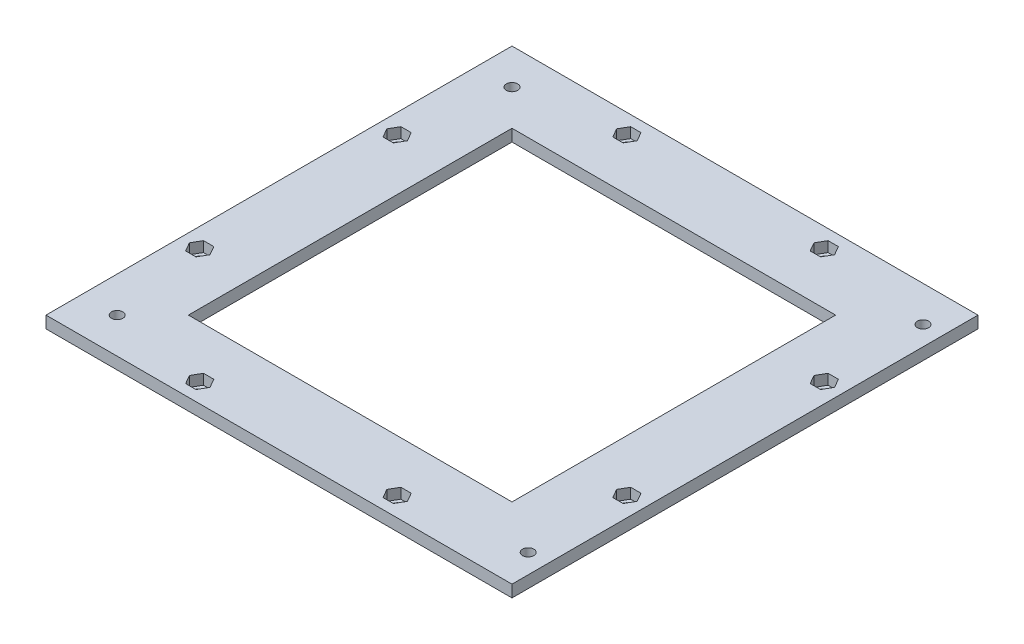
SolidWorks part; units mm, degrees
ref_plane "Alzado" through (0, 0, 0) normal (0, 0, 1) x (1, 0, 0)
ref_plane "Planta" through (0, 0, 0) normal (0, 1, 0) x (1, 0, 0)
ref_plane "Vista lateral" through (0, 0, 0) normal (1, 0, 0) x (0, 0, -1)
sketch "Croquis1" plane through (0, 0, 0) normal (0, 1, 0) x (1, 0, 0)
  line L0 (0, 0) -> (-62.5, 0) construction
  line L1 (-62.5, 0) -> (-62.5, 55) construction
  line L2 (-62.5, 55) -> (-55, 62.5) construction
  line L3 (-55, 62.5) -> (0, 62.5) construction
  line L4 (0, 62.5) -> (0, 0) construction
  line L5 (62.5, 55) -> (62.5, 0) construction
  line L6 (55, 62.5) -> (62.5, 55) construction
  line L7 (0, 62.5) -> (55, 62.5) construction
  line L8 (55, -62.5) -> (0, -62.5) construction
  line L9 (62.5, -55) -> (55, -62.5) construction
  line L10 (62.5, 0) -> (62.5, -55) construction
  line L11 (-62.5, -55) -> (-62.5, 0) construction
  line L12 (-55, -62.5) -> (-62.5, -55) construction
  line L13 (0, -62.5) -> (-55, -62.5) construction
  line L14 (0, -70) -> (0, -62.5) construction
  line L15 (0, 0) -> (-61, 0) construction
  line L16 (0, 0) -> (0, 61) construction
  line L17 (0, 61) -> (-61, 61) construction
  line L18 (-61, 0) -> (-61, 61) construction
  line L19 (0, 0) -> (-61, 0) construction
  line L20 (0, 0) -> (0, -61) construction
  line L21 (0, -61) -> (-61, -61) construction
  line L22 (-61, 0) -> (-61, -61) construction
  line L23 (0, 0) -> (66, 0) construction
  line L24 (0, 0) -> (0, -61) construction
  line L25 (0, -61) -> (66, -61) construction
  line L26 (66, 0) -> (66, -61) construction
  line L27 (0, 0) -> (66, 0) construction
  line L28 (0, 0) -> (0, 61) construction
  line L29 (0, 61) -> (66, 61) construction
  line L30 (66, 0) -> (66, 61) construction
  line L35 (25, -25) -> (-25, 25) construction
  line L36 (25, 25) -> (-25, -25) construction
  line L37 (70, -70) -> (-70, -70)
  line L38 (70, -70) -> (70, 70)
  line L39 (70, 70) -> (-70, 70)
  line L40 (-70, -70) -> (-70, 70)
  line L41 (70, -70) -> (-70, 70) construction
  line L42 (70, 70) -> (-70, -70) construction
  line L43 (-30.5, -66) -> (30.5, -66) construction
  circle A0 centre (-61, 61) radius 1.5
  circle A1 centre (66, 61) radius 1.5
  circle A2 centre (66, -61) radius 1.5
  circle A3 centre (-61, -61) radius 1.5
  circle A4 centre (66, 30.5) radius 1.5
  circle A5 centre (66, -30.5) radius 1.5
  circle A6 centre (-30.5, -66) radius 1.5
  circle A7 centre (30.5, -66) radius 1.5
  circle A8 centre (-30.5, 66) radius 1.5
  circle A9 centre (30.5, 66) radius 1.5
  circle A10 centre (-66, 30.5) radius 1.5
  circle A11 centre (-66, -30.5) radius 1.5
  point P48 (0, -66)
  dimension "D6" = 3
  dimension "D9" = 4
  dimension "D10" = 3
  dimension "D1" = 55
  dimension "D2" = 62.5
  dimension "D4" = 61
  dimension "D5" = 66
  dimension "D7" = 50
  dimension "D8" = 140
  dimension "D11" = 61
  dimension "D3" = 4
extrude "Saliente-Extruir1" add sketch "Croquis1" along normal blind 0.5
sketch "Croquis2" plane through (0, 0.5, 0) normal (0, 1, 0) x (1, 0, 0)
  line L1 (-28.9065, 63.24) -> (-27.313, 66)
  line L2 (-27.313, 66) -> (-28.9065, 68.76)
  line L3 (-28.9065, 68.76) -> (-32.0935, 68.76)
  line L4 (-32.0935, 68.76) -> (-33.687, 66)
  line L5 (-33.687, 66) -> (-32.0935, 63.24)
  line L6 (-32.0935, 63.24) -> (-28.9065, 63.24)
  line L7 (32.0935, 63.24) -> (33.687, 66)
  line L8 (33.687, 66) -> (32.0935, 68.76)
  line L9 (32.0935, 68.76) -> (28.9065, 68.76)
  line L10 (28.9065, 68.76) -> (27.313, 66)
  line L11 (27.313, 66) -> (28.9065, 63.24)
  line L12 (28.9065, 63.24) -> (32.0935, 63.24)
  line L13 (67.5935, 27.74) -> (69.187, 30.5)
  line L14 (69.187, 30.5) -> (67.5935, 33.26)
  line L15 (67.5935, 33.26) -> (64.4065, 33.26)
  line L16 (64.4065, 33.26) -> (62.813, 30.5)
  line L17 (62.813, 30.5) -> (64.4065, 27.74)
  line L18 (64.4065, 27.74) -> (67.5935, 27.74)
  line L19 (67.5935, -33.26) -> (69.187, -30.5)
  line L20 (69.187, -30.5) -> (67.5935, -27.74)
  line L21 (67.5935, -27.74) -> (64.4065, -27.74)
  line L22 (64.4065, -27.74) -> (62.813, -30.5)
  line L23 (62.813, -30.5) -> (64.4065, -33.26)
  line L24 (64.4065, -33.26) -> (67.5935, -33.26)
  line L25 (32.0935, -68.76) -> (33.687, -66)
  line L26 (33.687, -66) -> (32.0935, -63.24)
  line L27 (32.0935, -63.24) -> (28.9065, -63.24)
  line L28 (28.9065, -63.24) -> (27.313, -66)
  line L29 (27.313, -66) -> (28.9065, -68.76)
  line L30 (28.9065, -68.76) -> (32.0935, -68.76)
  line L31 (-28.9065, -68.76) -> (-27.313, -66)
  line L32 (-27.313, -66) -> (-28.9065, -63.24)
  line L33 (-28.9065, -63.24) -> (-32.0935, -63.24)
  line L34 (-32.0935, -63.24) -> (-33.687, -66)
  line L35 (-33.687, -66) -> (-32.0935, -68.76)
  line L36 (-32.0935, -68.76) -> (-28.9065, -68.76)
  line L37 (-64.4065, -33.26) -> (-62.813, -30.5)
  line L38 (-62.813, -30.5) -> (-64.4065, -27.74)
  line L39 (-64.4065, -27.74) -> (-67.5935, -27.74)
  line L40 (-67.5935, -27.74) -> (-69.187, -30.5)
  line L41 (-69.187, -30.5) -> (-67.5935, -33.26)
  line L42 (-67.5935, -33.26) -> (-64.4065, -33.26)
  line L43 (-64.4065, 27.74) -> (-62.813, 30.5)
  line L44 (-62.813, 30.5) -> (-64.4065, 33.26)
  line L45 (-64.4065, 33.26) -> (-67.5935, 33.26)
  line L46 (-67.5935, 33.26) -> (-69.187, 30.5)
  line L47 (-69.187, 30.5) -> (-67.5935, 27.74)
  line L48 (-67.5935, 27.74) -> (-64.4065, 27.74)
  line L49 (-50, 50) -> (50, 50)
  line L50 (-50, 50) -> (-50, -50)
  line L51 (-50, -50) -> (50, -50)
  line L52 (50, 50) -> (50, -50)
  line L53 (-50, 50) -> (50, -50) construction
  line L54 (-50, -50) -> (50, 50) construction
  circle A0 centre (-30.5, 66) radius 2.76 construction
  circle A1 centre (30.5, 66) radius 2.76 construction
  circle A2 centre (66, 30.5) radius 2.76 construction
  circle A3 centre (66, -30.5) radius 2.76 construction
  circle A4 centre (30.5, -66) radius 2.76 construction
  circle A5 centre (-30.5, -66) radius 2.76 construction
  circle A6 centre (-66, -30.5) radius 2.76 construction
  circle A7 centre (-66, 30.5) radius 2.76 construction
  circle A8 centre (66, 61) radius 1.75
  circle A9 centre (-61, 61) radius 1.75
  circle A10 centre (-61, -61) radius 1.75
  circle A11 centre (66, -61) radius 1.75
  point P64 (0, 0)
  dimension "D3" = 3.5
  dimension "D1" = 5.52
  dimension "D2" = 100
extrude "Cortar-Extruir1" cut sketch "Croquis2" against normal blind 10
sketch "Croquis3" plane through (0, 0.5, 0) normal (0, 1, 0) x (1, 0, 0)
  line L0 (-50, -50) -> (50, -50) construction
  line L1 (-50, 50) -> (-50, -50) construction
  line L12 (-33.687, -66) -> (-32.0935, -68.76) construction
  line L13 (-32.0935, -68.76) -> (-28.9065, -68.76) construction
  line L14 (-28.9065, -68.76) -> (-27.313, -66) construction
  line L15 (-27.313, -66) -> (-28.9065, -63.24) construction
  line L16 (-28.9065, -63.24) -> (-32.0935, -63.24) construction
  line L17 (-32.0935, -63.24) -> (-33.687, -66) construction
  line L18 (-67.5935, -33.26) -> (-64.4065, -33.26) construction
  line L19 (-69.187, -30.5) -> (-67.5935, -33.26) construction
  line L20 (-67.5935, -27.74) -> (-69.187, -30.5) construction
  line L21 (-64.4065, -27.74) -> (-67.5935, -27.74) construction
  line L22 (-62.813, -30.5) -> (-64.4065, -27.74) construction
  line L23 (-64.4065, -33.26) -> (-62.813, -30.5) construction
  line L24 (-50, 50) -> (-50, -50)
  line L25 (-50, -50) -> (50, -50)
  line L26 (-33.687, -66) -> (-32.0935, -68.76)
  line L27 (-32.0935, -68.76) -> (-28.9065, -68.76)
  line L28 (-28.9065, -68.76) -> (-27.313, -66)
  line L29 (-27.313, -66) -> (-28.9065, -63.24)
  line L30 (-28.9065, -63.24) -> (-32.0935, -63.24)
  line L31 (-32.0935, -63.24) -> (-33.687, -66)
  line L32 (-67.5935, -33.26) -> (-64.4065, -33.26)
  line L33 (-69.187, -30.5) -> (-67.5935, -33.26)
  line L34 (-67.5935, -27.74) -> (-69.187, -30.5)
  line L35 (-64.4065, -27.74) -> (-67.5935, -27.74)
  line L36 (-62.813, -30.5) -> (-64.4065, -27.74)
  line L37 (-64.4065, -33.26) -> (-62.813, -30.5)
  line L38 (28.9065, 63.24) -> (32.0935, 63.24) construction
  line L39 (32.0935, 63.24) -> (33.687, 66) construction
  line L40 (33.687, 66) -> (32.0935, 68.76) construction
  line L41 (32.0935, 68.76) -> (28.9065, 68.76) construction
  line L42 (28.9065, 68.76) -> (27.313, 66) construction
  line L43 (27.313, 66) -> (28.9065, 63.24) construction
  line L44 (-33.687, 66) -> (-32.0935, 63.24) construction
  line L45 (-32.0935, 68.76) -> (-33.687, 66) construction
  line L46 (-28.9065, 68.76) -> (-32.0935, 68.76) construction
  line L47 (-27.313, 66) -> (-28.9065, 68.76) construction
  line L48 (-28.9065, 63.24) -> (-27.313, 66) construction
  line L49 (-32.0935, 63.24) -> (-28.9065, 63.24) construction
  line L50 (62.813, 30.5) -> (64.4065, 27.74) construction
  line L51 (64.4065, 27.74) -> (67.5935, 27.74) construction
  line L52 (67.5935, 27.74) -> (69.187, 30.5) construction
  line L53 (69.187, 30.5) -> (67.5935, 33.26) construction
  line L54 (64.4065, 33.26) -> (62.813, 30.5) construction
  line L55 (67.5935, 33.26) -> (64.4065, 33.26) construction
  line L56 (67.5935, -33.26) -> (69.187, -30.5) construction
  line L57 (69.187, -30.5) -> (67.5935, -27.74) construction
  line L58 (67.5935, -27.74) -> (64.4065, -27.74) construction
  line L59 (64.4065, -27.74) -> (62.813, -30.5) construction
  line L60 (62.813, -30.5) -> (64.4065, -33.26) construction
  line L61 (64.4065, -33.26) -> (67.5935, -33.26) construction
  line L62 (33.687, -66) -> (32.0935, -63.24) construction
  line L63 (32.0935, -68.76) -> (33.687, -66) construction
  line L64 (28.9065, -68.76) -> (32.0935, -68.76) construction
  line L65 (27.313, -66) -> (28.9065, -68.76) construction
  line L66 (50, -50) -> (50, 50) construction
  line L67 (28.9065, -63.24) -> (27.313, -66) construction
  line L68 (32.0935, -63.24) -> (28.9065, -63.24) construction
  line L69 (28.9065, 63.24) -> (32.0935, 63.24)
  line L70 (32.0935, 63.24) -> (33.687, 66)
  line L71 (33.687, 66) -> (32.0935, 68.76)
  line L72 (32.0935, 68.76) -> (28.9065, 68.76)
  line L73 (28.9065, 68.76) -> (27.313, 66)
  line L74 (27.313, 66) -> (28.9065, 63.24)
  line L75 (-33.687, 66) -> (-32.0935, 63.24)
  line L76 (-32.0935, 68.76) -> (-33.687, 66)
  line L77 (-28.9065, 68.76) -> (-32.0935, 68.76)
  line L78 (-27.313, 66) -> (-28.9065, 68.76)
  line L79 (-28.9065, 63.24) -> (-27.313, 66)
  line L80 (-32.0935, 63.24) -> (-28.9065, 63.24)
  line L81 (62.813, 30.5) -> (64.4065, 27.74)
  line L82 (64.4065, 27.74) -> (67.5935, 27.74)
  line L83 (67.5935, 27.74) -> (69.187, 30.5)
  line L84 (69.187, 30.5) -> (67.5935, 33.26)
  line L85 (64.4065, 33.26) -> (62.813, 30.5)
  line L86 (67.5935, 33.26) -> (64.4065, 33.26)
  line L87 (67.5935, -33.26) -> (69.187, -30.5)
  line L88 (69.187, -30.5) -> (67.5935, -27.74)
  line L89 (67.5935, -27.74) -> (64.4065, -27.74)
  line L90 (64.4065, -27.74) -> (62.813, -30.5)
  line L91 (62.813, -30.5) -> (64.4065, -33.26)
  line L92 (64.4065, -33.26) -> (67.5935, -33.26)
  line L93 (33.687, -66) -> (32.0935, -63.24)
  line L94 (32.0935, -68.76) -> (33.687, -66)
  line L95 (28.9065, -68.76) -> (32.0935, -68.76)
  line L96 (27.313, -66) -> (28.9065, -68.76)
  line L97 (50, -50) -> (50, 50)
  line L98 (28.9065, -63.24) -> (27.313, -66)
  line L99 (32.0935, -63.24) -> (28.9065, -63.24)
  line L100 (-64.4065, 27.74) -> (-62.813, 30.5) construction
  line L101 (-67.5935, 27.74) -> (-64.4065, 27.74) construction
  line L102 (-69.187, 30.5) -> (-67.5935, 27.74) construction
  line L103 (-67.5935, 33.26) -> (-69.187, 30.5) construction
  line L104 (-64.4065, 33.26) -> (-67.5935, 33.26) construction
  line L105 (-62.813, 30.5) -> (-64.4065, 33.26) construction
  line L106 (-64.4065, 27.74) -> (-62.813, 30.5)
  line L107 (-67.5935, 27.74) -> (-64.4065, 27.74)
  line L108 (-69.187, 30.5) -> (-67.5935, 27.74)
  line L109 (-67.5935, 33.26) -> (-69.187, 30.5)
  line L110 (-64.4065, 33.26) -> (-67.5935, 33.26)
  line L111 (-62.813, 30.5) -> (-64.4065, 33.26)
  line L112 (50, 50) -> (-50, 50) construction
  line L113 (50, 50) -> (-50, 50)
  line L116 (-72, -72) -> (72, -72)
  line L117 (-72, 72) -> (-72, -72)
  line L118 (72, 72) -> (-72, 72)
  line L119 (72, -72) -> (72, 72)
  line L120 (-72, -72) -> (72, -72)
  line L121 (-72, 72) -> (-72, -72)
  line L122 (72, 72) -> (-72, 72)
  line L123 (72, -72) -> (72, 72)
  circle A0 centre (-61, -61) radius 1.75 construction
  circle A1 centre (-61, -61) radius 1.75
  circle A2 centre (-61, 61) radius 1.75 construction
  circle A3 centre (66, 61) radius 1.75 construction
  circle A4 centre (66, -61) radius 1.75 construction
  circle A5 centre (-61, 61) radius 1.75
  circle A6 centre (66, 61) radius 1.75
  circle A7 centre (66, -61) radius 1.75
  dimension "D1" = 2
extrude "Saliente-Extruir3" add sketch "Croquis3" along normal blind 2.7
sketch "Croquis4" plane through (0, 0.5, 0) normal (0, -1, 0) x (1, 0, 0)
  line L0 (-70, 70) -> (70, 70) construction
  line L1 (70, 70) -> (70, -70) construction
  line L2 (70, -70) -> (-70, -70) construction
  line L3 (-70, -70) -> (-70, 70) construction
  line L4 (72, 72) -> (-72, 72)
  line L5 (-72, 72) -> (-72, -72)
  line L6 (-72, -72) -> (72, -72)
  line L7 (72, -72) -> (72, 72)
  line L8 (72, 72) -> (-72, 72)
  line L9 (-72, 72) -> (-72, -72)
  line L10 (-72, -72) -> (72, -72)
  line L11 (72, -72) -> (72, 72)
  line L12 (-70, 70) -> (70, 70)
  line L13 (70, 70) -> (70, -70)
  line L14 (70, -70) -> (-70, -70)
  line L15 (-70, -70) -> (-70, 70)
  dimension "D1" = 0
extrude "Saliente-Extruir4" add sketch "Croquis4" along normal blind 0.5
sketch "Croquis5" plane through (0, 0, 0) normal (0, -1, 0) x (1, 0, 0)
  line L0 (66, -27.74) -> (66, -33.26) construction
  line L1 (64.4065, -27.74) -> (67.5935, -27.74) construction
  line L2 (67.5935, -33.26) -> (64.4065, -33.26) construction
  line L3 (30.5, -68.76) -> (30.5, -63.24) construction
  line L4 (32.0935, -68.76) -> (28.9065, -68.76) construction
  line L5 (28.9065, -63.24) -> (32.0935, -63.24) construction
  line L6 (-30.5, -68.76) -> (-30.5, -63.24) construction
  line L7 (-28.9065, -68.76) -> (-32.0935, -68.76) construction
  line L8 (-32.0935, -63.24) -> (-28.9065, -63.24) construction
  line L9 (-66, -33.26) -> (-66, -27.74) construction
  line L10 (-64.4065, -33.26) -> (-67.5935, -33.26) construction
  line L11 (-67.5935, -27.74) -> (-64.4065, -27.74) construction
  line L12 (-66, 27.74) -> (-66, 33.26) construction
  line L13 (-64.4065, 27.74) -> (-67.5935, 27.74) construction
  line L14 (-67.5935, 33.26) -> (-64.4065, 33.26) construction
  line L15 (-30.5, 63.24) -> (-30.5, 68.76) construction
  line L16 (-28.9065, 63.24) -> (-32.0935, 63.24) construction
  line L17 (-32.0935, 68.76) -> (-28.9065, 68.76) construction
  line L18 (30.5, 63.24) -> (30.5, 68.76) construction
  line L19 (32.0935, 63.24) -> (28.9065, 63.24) construction
  line L20 (28.9065, 68.76) -> (32.0935, 68.76) construction
  line L21 (66, 27.74) -> (66, 33.26) construction
  line L22 (67.5935, 27.74) -> (64.4065, 27.74) construction
  line L23 (64.4065, 33.26) -> (67.5935, 33.26) construction
  line L24 (-50, -50) -> (-50, 50) construction
  line L25 (-50, 50) -> (50, 50) construction
  line L26 (50, 50) -> (50, -50) construction
  line L27 (50, -50) -> (-50, -50) construction
  line L28 (72, -72) -> (72, 72)
  line L29 (72, 72) -> (-72, 72)
  line L30 (-72, 72) -> (-72, -72)
  line L31 (-72, -72) -> (72, -72)
  line L32 (72, -72) -> (72, 72)
  line L33 (72, 72) -> (-72, 72)
  line L34 (-72, 72) -> (-72, -72)
  line L35 (-72, -72) -> (72, -72)
  line L36 (-50, -50) -> (-50, 50)
  line L37 (-50, 50) -> (50, 50)
  line L38 (50, 50) -> (50, -50)
  line L39 (50, -50) -> (-50, -50)
  circle A0 centre (66, -61) radius 1.75 construction
  circle A1 centre (-61, -61) radius 1.75 construction
  circle A2 centre (66, 61) radius 1.75 construction
  circle A3 centre (-61, 61) radius 1.75 construction
  circle A4 centre (66, -61) radius 1.75
  circle A5 centre (-61, -61) radius 1.75
  circle A6 centre (66, 61) radius 1.75
  circle A7 centre (-61, 61) radius 1.75
  circle A8 centre (66, 30.5) radius 1.75
  circle A9 centre (30.5, 66) radius 1.75
  circle A10 centre (-30.5, 66) radius 1.75
  circle A11 centre (-66, 30.5) radius 1.75
  circle A12 centre (-66, -30.5) radius 1.75
  circle A13 centre (-30.5, -66) radius 1.75
  circle A14 centre (30.5, -66) radius 1.75
  circle A15 centre (66, -30.5) radius 1.75
  dimension "D1" = 0
extrude "Saliente-Extruir5" add sketch "Croquis5" along normal blind 0.5
